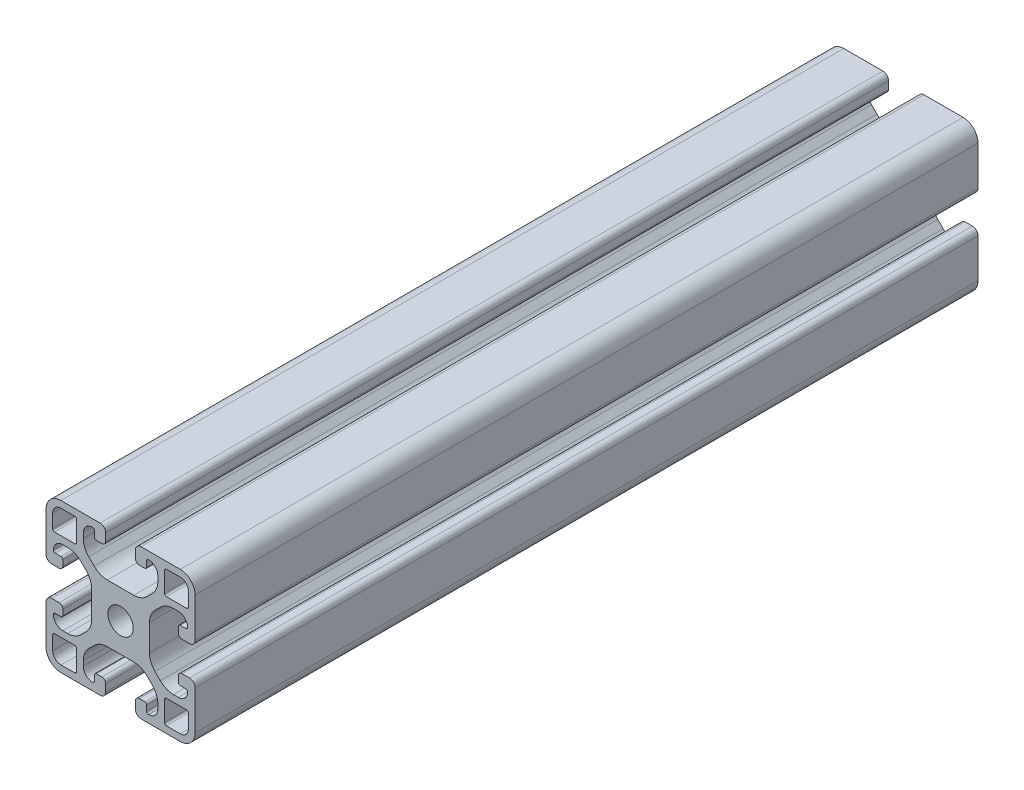
SolidWorks part; units mm, degrees
ref_plane "Plan de face" through (0, 0, 0) normal (0, 0, 1) x (1, 0, 0)
ref_plane "Plan de dessus" through (0, 0, 0) normal (0, 1, 0) x (1, 0, 0)
ref_plane "Plan de droite" through (0, 0, 0) normal (1, 0, 0) x (0, 0, -1)
ref_plane "Plan1" through (0, 0, -30) normal (0, 0, -1) x (-1, 0, 0)
sketch "Esquisse1" plane through (0, 0, -30) normal (0, 0, -1) x (-1, 0, 0)
  line L0 (-4.5, 15) -> (-4.5, 13.5)
  line L1 (-4, 13) -> (-2.5, 13)
  line L2 (-4.5, 10) -> (-5.8076, 10)
  line L3 (-9.3431, 11.4645) -> (-10.7855, 12.9069)
  line L4 (-12.25, 16.4424) -> (-12.25, 23.5576)
  line L5 (-10.7855, 27.0931) -> (-9.3431, 28.5355)
  line L6 (-5.8076, 30) -> (-4.5, 30)
  line L7 (-2.5, 27) -> (-4, 27)
  line L8 (-4.5, 26.5) -> (-4.5, 25)
  line L9 (-3.5, 24) -> (-1.5, 24)
  line L10 (0, 25.5) -> (0, 36)
  line L11 (-4, 40) -> (-14.5, 40)
  line L12 (-16, 38.5) -> (-16, 36.5)
  line L13 (-15, 35.5) -> (-13.5, 35.5)
  line L14 (-13, 36) -> (-13, 37.5)
  line L15 (-10, 35.5) -> (-10, 34.1924)
  line L16 (-11.4645, 30.6569) -> (-12.9069, 29.2145)
  line L17 (-16.4424, 27.75) -> (-23.5576, 27.75)
  line L18 (-27.0931, 29.2145) -> (-28.5355, 30.6569)
  line L19 (-30, 34.1924) -> (-30, 35.5)
  line L20 (-27, 37.5) -> (-27, 36)
  line L21 (-26.5, 35.5) -> (-25, 35.5)
  line L22 (-24, 36.5) -> (-24, 38.5)
  line L23 (-25.5, 40) -> (-36, 40)
  line L24 (-40, 36) -> (-40, 25.5)
  line L25 (-38.5, 24) -> (-36.5, 24)
  line L26 (-35.5, 25) -> (-35.5, 26.5)
  line L27 (-36, 27) -> (-37.5, 27)
  line L28 (-35.5, 30) -> (-34.1924, 30)
  line L29 (-30.6569, 28.5355) -> (-29.2145, 27.0931)
  line L30 (-27.75, 23.5576) -> (-27.75, 16.4424)
  line L31 (-29.2145, 12.9069) -> (-30.6569, 11.4645)
  line L32 (-34.1924, 10) -> (-35.5, 10)
  line L33 (-37.5, 13) -> (-36, 13)
  line L34 (-35.5, 13.5) -> (-35.5, 15)
  line L35 (-36.5, 16) -> (-38.5, 16)
  line L36 (-40, 14.5) -> (-40, 4)
  line L37 (-36, 0) -> (-25.5, 0)
  line L38 (-24, 1.5) -> (-24, 3.5)
  line L39 (-25, 4.5) -> (-26.5, 4.5)
  line L40 (-27, 4) -> (-27, 2.5)
  line L41 (-30, 4.5) -> (-30, 5.8076)
  line L42 (-28.5355, 9.3431) -> (-27.0931, 10.7855)
  line L43 (-23.5576, 12.25) -> (-16.4424, 12.25)
  line L44 (-12.9069, 10.7855) -> (-11.4645, 9.3431)
  line L45 (-10, 5.8076) -> (-10, 4.5)
  line L46 (-13, 2.5) -> (-13, 4)
  line L47 (-13.5, 4.5) -> (-15, 4.5)
  line L48 (-16, 3.5) -> (-16, 1.5)
  line L49 (-14.5, 0) -> (-4, 0)
  line L50 (0, 4) -> (0, 14.5)
  line L51 (-1.5, 16) -> (-3.5, 16)
  line L52 (-4, 1.8) -> (-7.7, 1.8)
  line L53 (-8.2, 2.3) -> (-8.2, 7.7)
  line L54 (-7.7, 8.2) -> (-2.3, 8.2)
  line L55 (-1.8, 7.7) -> (-1.8, 4)
  line L56 (-38.2, 4) -> (-38.2, 7.7)
  line L57 (-37.7, 8.2) -> (-32.3, 8.2)
  line L58 (-31.8, 7.7) -> (-31.8, 2.3)
  line L59 (-32.3, 1.8) -> (-36, 1.8)
  line L60 (-36, 38.2) -> (-32.3, 38.2)
  line L61 (-31.8, 37.7) -> (-31.8, 32.3)
  line L62 (-32.3, 31.8) -> (-37.7, 31.8)
  line L63 (-38.2, 32.3) -> (-38.2, 36)
  line L64 (-1.8, 36) -> (-1.8, 32.3)
  line L65 (-2.3, 31.8) -> (-7.7, 31.8)
  line L66 (-8.2, 32.3) -> (-8.2, 37.7)
  line L67 (-7.7, 38.2) -> (-4, 38.2)
  arc A0 (-4.5, 13.5) -> (-4, 13) centre (-4, 13.5) ccw
  arc A1 (-2.5, 13) -> (-2, 12.5) centre (-2.5, 12.5) cw
  arc A2 (-2, 12.5) -> (-4.5, 10) centre (-4.5, 12.5) cw
  arc A3 (-5.8076, 10) -> (-9.3431, 11.4645) centre (-5.8076, 15) cw
  arc A4 (-10.7855, 12.9069) -> (-12.25, 16.4424) centre (-7.25, 16.4424) cw
  arc A5 (-12.25, 23.5576) -> (-10.7855, 27.0931) centre (-7.25, 23.5576) cw
  arc A6 (-9.3431, 28.5355) -> (-5.8076, 30) centre (-5.8076, 25) cw
  arc A7 (-4.5, 30) -> (-2, 27.5) centre (-4.5, 27.5) cw
  arc A8 (-2, 27.5) -> (-2.5, 27) centre (-2.5, 27.5) cw
  arc A9 (-4, 27) -> (-4.5, 26.5) centre (-4, 26.5) ccw
  arc A10 (-4.5, 25) -> (-3.5, 24) centre (-3.5, 25) ccw
  arc A11 (-1.5, 24) -> (0, 25.5) centre (-1.5, 25.5) ccw
  arc A12 (0, 36) -> (-4, 40) centre (-4, 36) ccw
  arc A13 (-14.5, 40) -> (-16, 38.5) centre (-14.5, 38.5) ccw
  arc A14 (-16, 36.5) -> (-15, 35.5) centre (-15, 36.5) ccw
  arc A15 (-13.5, 35.5) -> (-13, 36) centre (-13.5, 36) ccw
  arc A16 (-13, 37.5) -> (-12.5, 38) centre (-12.5, 37.5) cw
  arc A17 (-12.5, 38) -> (-10, 35.5) centre (-12.5, 35.5) cw
  arc A18 (-10, 34.1924) -> (-11.4645, 30.6569) centre (-15, 34.1924) cw
  arc A19 (-12.9069, 29.2145) -> (-16.4424, 27.75) centre (-16.4424, 32.75) cw
  arc A20 (-23.5576, 27.75) -> (-27.0931, 29.2145) centre (-23.5576, 32.75) cw
  arc A21 (-28.5355, 30.6569) -> (-30, 34.1924) centre (-25, 34.1924) cw
  arc A22 (-30, 35.5) -> (-27.5, 38) centre (-27.5, 35.5) cw
  arc A23 (-27.5, 38) -> (-27, 37.5) centre (-27.5, 37.5) cw
  arc A24 (-27, 36) -> (-26.5, 35.5) centre (-26.5, 36) ccw
  arc A25 (-25, 35.5) -> (-24, 36.5) centre (-25, 36.5) ccw
  arc A26 (-24, 38.5) -> (-25.5, 40) centre (-25.5, 38.5) ccw
  arc A27 (-36, 40) -> (-40, 36) centre (-36, 36) ccw
  arc A28 (-40, 25.5) -> (-38.5, 24) centre (-38.5, 25.5) ccw
  arc A29 (-36.5, 24) -> (-35.5, 25) centre (-36.5, 25) ccw
  arc A30 (-35.5, 26.5) -> (-36, 27) centre (-36, 26.5) ccw
  arc A31 (-37.5, 27) -> (-38, 27.5) centre (-37.5, 27.5) cw
  arc A32 (-38, 27.5) -> (-35.5, 30) centre (-35.5, 27.5) cw
  arc A33 (-34.1924, 30) -> (-30.6569, 28.5355) centre (-34.1924, 25) cw
  arc A34 (-29.2145, 27.0931) -> (-27.75, 23.5576) centre (-32.75, 23.5576) cw
  arc A35 (-27.75, 16.4424) -> (-29.2145, 12.9069) centre (-32.75, 16.4424) cw
  arc A36 (-30.6569, 11.4645) -> (-34.1924, 10) centre (-34.1924, 15) cw
  arc A37 (-35.5, 10) -> (-38, 12.5) centre (-35.5, 12.5) cw
  arc A38 (-38, 12.5) -> (-37.5, 13) centre (-37.5, 12.5) cw
  arc A39 (-36, 13) -> (-35.5, 13.5) centre (-36, 13.5) ccw
  arc A40 (-35.5, 15) -> (-36.5, 16) centre (-36.5, 15) ccw
  arc A41 (-38.5, 16) -> (-40, 14.5) centre (-38.5, 14.5) ccw
  arc A42 (-40, 4) -> (-36, 0) centre (-36, 4) ccw
  arc A43 (-25.5, 0) -> (-24, 1.5) centre (-25.5, 1.5) ccw
  arc A44 (-24, 3.5) -> (-25, 4.5) centre (-25, 3.5) ccw
  arc A45 (-26.5, 4.5) -> (-27, 4) centre (-26.5, 4) ccw
  arc A46 (-27, 2.5) -> (-27.5, 2) centre (-27.5, 2.5) cw
  arc A47 (-27.5, 2) -> (-30, 4.5) centre (-27.5, 4.5) cw
  arc A48 (-30, 5.8076) -> (-28.5355, 9.3431) centre (-25, 5.8076) cw
  arc A49 (-27.0931, 10.7855) -> (-23.5576, 12.25) centre (-23.5576, 7.25) cw
  arc A50 (-16.4424, 12.25) -> (-12.9069, 10.7855) centre (-16.4424, 7.25) cw
  arc A51 (-11.4645, 9.3431) -> (-10, 5.8076) centre (-15, 5.8076) cw
  arc A52 (-10, 4.5) -> (-12.5, 2) centre (-12.5, 4.5) cw
  arc A53 (-12.5, 2) -> (-13, 2.5) centre (-12.5, 2.5) cw
  arc A54 (-13, 4) -> (-13.5, 4.5) centre (-13.5, 4) ccw
  arc A55 (-15, 4.5) -> (-16, 3.5) centre (-15, 3.5) ccw
  arc A56 (-16, 1.5) -> (-14.5, 0) centre (-14.5, 1.5) ccw
  arc A57 (-4, 0) -> (0, 4) centre (-4, 4) ccw
  arc A58 (0, 14.5) -> (-1.5, 16) centre (-1.5, 14.5) ccw
  arc A59 (-3.5, 16) -> (-4.5, 15) centre (-3.5, 15) ccw
  circle A60 centre (-20, 20) radius 3.4
  arc A61 (-1.8, 4) -> (-4, 1.8) centre (-4, 4) cw
  arc A62 (-7.7, 1.8) -> (-8.2, 2.3) centre (-7.7, 2.3) cw
  arc A63 (-8.2, 7.7) -> (-7.7, 8.2) centre (-7.7, 7.7) cw
  arc A64 (-2.3, 8.2) -> (-1.8, 7.7) centre (-2.3, 7.7) cw
  arc A65 (-36, 1.8) -> (-38.2, 4) centre (-36, 4) cw
  arc A66 (-38.2, 7.7) -> (-37.7, 8.2) centre (-37.7, 7.7) cw
  arc A67 (-32.3, 8.2) -> (-31.8, 7.7) centre (-32.3, 7.7) cw
  arc A68 (-31.8, 2.3) -> (-32.3, 1.8) centre (-32.3, 2.3) cw
  arc A69 (-38.2, 36) -> (-36, 38.2) centre (-36, 36) cw
  arc A70 (-32.3, 38.2) -> (-31.8, 37.7) centre (-32.3, 37.7) cw
  arc A71 (-31.8, 32.3) -> (-32.3, 31.8) centre (-32.3, 32.3) cw
  arc A72 (-37.7, 31.8) -> (-38.2, 32.3) centre (-37.7, 32.3) cw
  arc A73 (-4, 38.2) -> (-1.8, 36) centre (-4, 36) cw
  arc A74 (-1.8, 32.3) -> (-2.3, 31.8) centre (-2.3, 32.3) cw
  arc A75 (-7.7, 31.8) -> (-8.2, 32.3) centre (-7.7, 32.3) cw
  arc A76 (-8.2, 37.7) -> (-7.7, 38.2) centre (-7.7, 37.7) cw
extrude "Boss.-Extru.1" add sketch "Esquisse1" against normal blind 210
